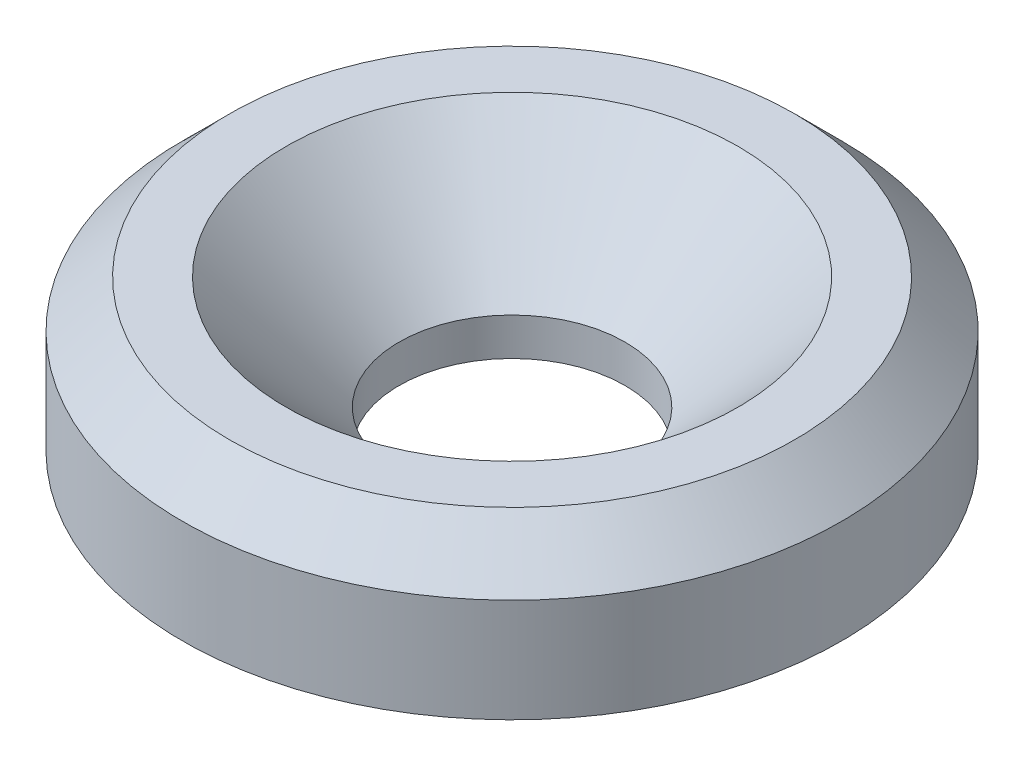
SolidWorks part; units mm, degrees
ref_plane "Front Plane" through (0, 0, 0) normal (0, 0, 1) x (1, 0, 0)
ref_plane "Top Plane" through (0, 0, 0) normal (0, 1, 0) x (1, 0, 0)
ref_plane "Right Plane" through (0, 0, 0) normal (1, 0, 0) x (0, 0, -1)
sketch "Sketch1" plane through (0, 0, 0) normal (0, 0, 1) x (1, 0, 0)
  line L0 (-6, 0) -> (-6, 2)
  line L1 (-6, 2) -> (-12, 8)
  line L2 (-12, 8) -> (-17.5, 8)
  line L3 (-17.5, 8) -> (-17.5, 0)
  line L4 (-17.5, 0) -> (-6, 0)
  line L5 (0, 0) -> (0, 19.0062) construction
  dimension "D1" = 8
  dimension "D2" = 45
  dimension "D3" = 6
  dimension "D4" = 2
  dimension "D5" = 17.5
revolve "Revolve1" add sketch "Sketch1" angle 360 about L5
chamfer "Chamfer1" distance 2.5 angle 45 1 edges at (0, 8, -17.5)
